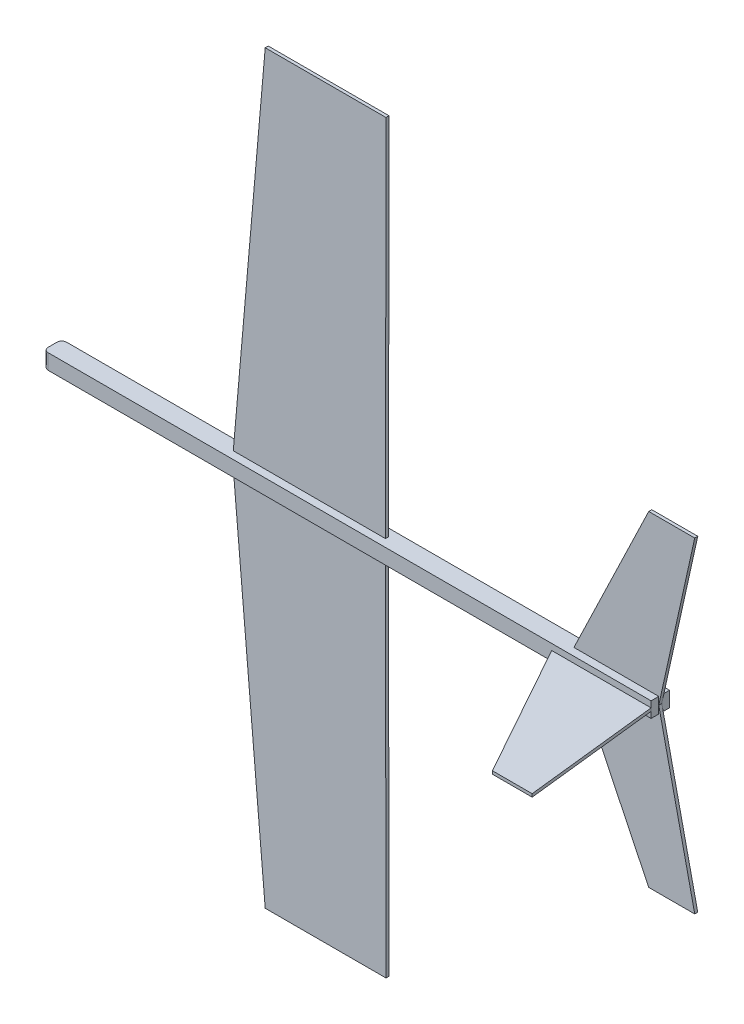
SolidWorks part; units mm, degrees
ref_plane "Front Plane" through (0, 0, 0) normal (0, 0, 1) x (1, 0, 0)
ref_plane "Top Plane" through (0, 0, 0) normal (0, 1, 0) x (1, 0, 0)
ref_plane "Right Plane" through (0, 0, 0) normal (1, 0, 0) x (0, 0, -1)
sketch "Sketch1" plane through (0, 0, 0) normal (0, 0, 1) x (1, 0, 0)
  line L0 (-159, 0) -> (159, 0) construction
  line L1 (159, 4) -> (-159, 4)
  line L2 (159, 4) -> (159, -4)
  line L3 (159, -4) -> (-159, -4)
  line L4 (-159, 4) -> (-159, -4)
  line L5 (159, 4) -> (-159, -4) construction
  line L6 (159, -4) -> (-159, 4) construction
  point P0 (0, 0)
  dimension "D1" = 8
  dimension "D2" = 318
extrude "Boss-Extrude1" add sketch "Sketch1" along normal mid plane 9.6
ref_plane "Plane3" through (0, 0, 0) normal (0, 0, 1) x (1, 0, 0)
sketch "Sketch3" plane through (0, 0, 0) normal (0, 0, 1) x (1, 0, 0)
  line L0 (-64, 0) -> (-46.9397, 195)
  line L1 (-46.9397, 195) -> (16.2603, 195)
  line L2 (16.2603, 195) -> (16, 0)
  line L3 (16, 0) -> (-64, 0)
  line L4 (-159, 4.2457) -> (-159, 3.7433) construction
  dimension "D1" = 95
  dimension "D2" = 80
  dimension "D3" = 63.2
  dimension "D4" = 195
  dimension "D5" = 85
extrude "Boss-Extrude2" add sketch "Sketch3" along normal mid plane 1.5875 contours L2 L3 L0 L1
mirror "Mirror1" about plane through (0, 0, 0) normal (0, 1, 0) of "Boss-Extrude2"
sketch "Sketch6" plane through (0, 0, 0) normal (0, 1, 0) x (1, 0, 0)
  line L0 (159, -4.8) -> (166.766, -74.8)
  line L1 (166.766, -74.8) -> (145.966, -74.8)
  line L2 (145.966, -74.8) -> (107, -4.8)
  line L3 (-159, -4.8) -> (159, -4.8) construction
  line L4 (107, -4.8) -> (159, -4.8)
  line L5 (151.166, -74.8) -> (120, -4.8) construction
  line L6 (159, -4.8) -> (-159, -4.8) construction
  dimension "D1" = 20.8
  dimension "D2" = 52
  dimension "D4" = 66
  dimension "D3" = 13
  dimension "D5" = 5.2
  dimension "D6" = 70
extrude "Boss-Extrude3" add sketch "Sketch6" along normal mid plane 1.5875 contours L0 L1 L2 L4
sketch "Sketch8" plane through (0, 0, 0) normal (0, 0, 1) x (1, 0, 0)
  line L0 (159, 0) -> (177.8349, 85.2)
  line L1 (5.28, 0) -> (-5.28, 0) construction
  line L2 (177.8349, 85.2) -> (153.7589, 85.2)
  line L3 (153.7589, 85.2) -> (112.7, 0)
  line L4 (112.7, 0) -> (159, 0)
  line L5 (159, -4) -> (159, -0.7937) construction
  dimension "D1" = 24.076
  dimension "D2" = 46.3
  dimension "D4" = 64.27
  dimension "D3" = 85.2
extrude "Boss-Extrude4" add sketch "Sketch8" along normal mid plane 1.5875 contours L0 L2 L3 L4
mirror "Mirror2" about plane through (0, 0, 0) normal (0, 1, 0) of "Boss-Extrude4"
fillet "Fillet1" radius 2.5 2 edges at (-159, 0, -4.8) (-159, 0, 4.8)
equation "\"Wing Root chord\"= 8cm"
equation "\"Taper Ratio\"= 0.79"
equation "\"Wing Tip chord\"= \"Wing Root chord\" * \"Taper Ratio\""
equation "\"D2@Sketch3\"=\"Wing Root chord\""
equation "\"D3@Sketch3\"=\"Wing Tip chord\""
equation "\"Vertical Wing Root chord\"= 5.2"
equation "\"Vertical Wing Taper Ratio\"= 0.4"
equation "\"Vertical Wing Tip chord\"= \"Vertical Wing Root chord\" * \"Vertical Wing Taper Ratio\""
equation "\"D1@Sketch6\"=\"Vertical Wing Tip chord\""
equation "\"D2@Sketch6\"=\"Vertical Wing Root chord\""
equation "\"Stabilizer Root Chord\"= 4.63cm"
equation "\"Stabilizer Taper Ratio\"= 0.52'S"
equation "\"Stabilizer Tip chord\"= \"Stabilizer Root Chord\" * \"Stabilizer Taper Ratio\""
equation "\"D1@Sketch8\"=\"Stabilizer Tip chord\""
equation "\"D2@Sketch8\"=\"Stabilizer Root Chord\""
